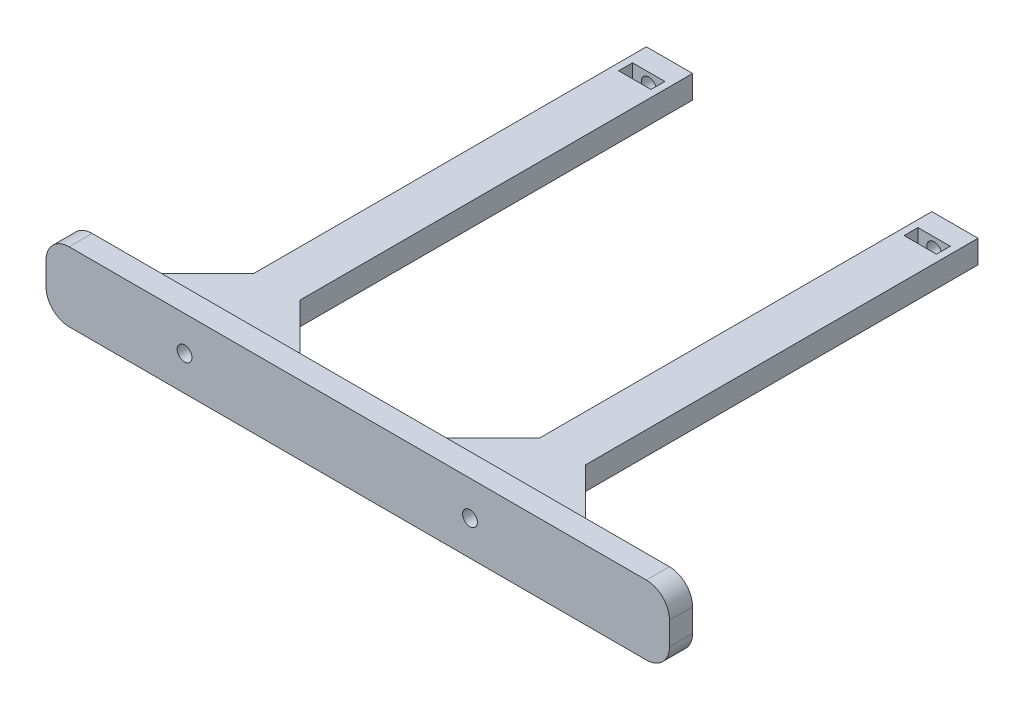
SolidWorks part; units mm, degrees
ref_plane "Plano frontal" through (0, 0, 0) normal (0, 0, 1) x (1, 0, 0)
ref_plane "Plano superior" through (0, 0, 0) normal (0, 1, 0) x (1, 0, 0)
ref_plane "Plano direito" through (0, 0, 0) normal (1, 0, 0) x (0, 0, -1)
sketch "Esboço1" plane through (0, 0, 0) normal (0, 0, 1) x (1, 0, 0)
  line L1 (-57.7659, 9.2429) -> (77.2341, 9.2429)
  line L2 (-57.7659, 9.2429) -> (-57.7659, -5.7571)
  line L3 (-57.7659, -5.7571) -> (77.2341, -5.7571)
  line L4 (77.2341, 9.2429) -> (77.2341, -5.7571)
extrude "Ressalto-extrusão1" add sketch "Esboço1" along normal blind 5
fillet "Filete1" radius 5 2 edges at (-57.7659, -5.7571, 2.5) (-57.7659, 9.2429, 2.5)
fillet "Filete2" radius 5 2 edges at (77.2341, 9.2429, 2.5) (77.2341, -5.7571, 2.5)
sketch "Esboço3" plane through (0, 0, 0) normal (0, 0, -1) x (-1, 0, 0)
  line L0 (57.7659, 1.7429) -> (27.7659, 1.7429) construction
  line L1 (57.7659, 4.2429) -> (57.7659, -0.7571) construction
  line L2 (27.7659, 1.7429) -> (-34.0341, 1.7429) construction
  circle A0 centre (27.7659, 1.7429) radius 1.6
  circle A1 centre (-34.0341, 1.7429) radius 1.6
extrude "Corte-extrusão1" cut sketch "Esboço3" against normal blind 5
sketch "Esboço5" plane through (0, 0, 0) normal (0, 0, -1) x (-1, 0, 0)
  line L1 (-39.0341, -0.7571) -> (-29.0341, -0.7571)
  line L2 (-39.0341, -0.7571) -> (-39.0341, 4.2429)
  line L3 (-39.0341, 4.2429) -> (-29.0341, 4.2429)
  line L4 (-29.0341, -0.7571) -> (-29.0341, 4.2429)
  line L5 (-39.0341, -0.7571) -> (-29.0341, 4.2429) construction
  line L6 (-39.0341, 4.2429) -> (-29.0341, -0.7571) construction
  line L7 (22.7659, -0.7571) -> (32.7659, -0.7571)
  line L8 (22.7659, -0.7571) -> (22.7659, 4.2429)
  line L9 (22.7659, 4.2429) -> (32.7659, 4.2429)
  line L10 (32.7659, -0.7571) -> (32.7659, 4.2429)
  line L11 (22.7659, -0.7571) -> (32.7659, 4.2429) construction
  line L12 (22.7659, 4.2429) -> (32.7659, -0.7571) construction
  point P0 (-34.0341, 1.7429)
  point P5 (27.7659, 1.7429)
extrude "Ressalto-extrusão4" add sketch "Esboço5" along normal blind 100
sketch "Esboço6" plane through (0, 4.2429, 0) normal (0, 1, 0) x (1, 0, 0)
  line L0 (34.0341, 100) -> (34.0341, 94) construction
  line L1 (29.0341, 100) -> (39.0341, 100) construction
  line L2 (-27.7659, 100) -> (-27.7659, 94) construction
  line L3 (-32.7659, 100) -> (-22.7659, 100) construction
  line L5 (37.5341, 95.5) -> (30.5341, 95.5)
  line L6 (37.5341, 95.5) -> (37.5341, 92.5)
  line L7 (37.5341, 92.5) -> (30.5341, 92.5)
  line L8 (30.5341, 95.5) -> (30.5341, 92.5)
  line L9 (37.5341, 95.5) -> (30.5341, 92.5) construction
  line L10 (37.5341, 92.5) -> (30.5341, 95.5) construction
ref_plane "Plano1" through (0, 1.7429, 0) normal (0, 1, 0) x (1, 0, 0)
sketch "Esboço7" plane through (0, 1.7429, 0) normal (0, 1, 0) x (1, 0, 0)
  line L0 (-32.7659, 100) -> (-32.7659, 0) construction
  line L1 (-32.7659, 15) -> (-32.7659, 0)
  line L2 (72.2341, 0) -> (-52.7659, 0) construction
  line L3 (-32.7659, 0) -> (-47.7659, 0)
  line L4 (-32.7659, 15) -> (-47.7659, 0)
extrude "Ressalto-extrusão5" add sketch "Esboço7" along normal up to vertex and the other way up to vertex
sketch "Esboço8" plane through (0, 4.2429, 0) normal (0, 1, 0) x (1, 0, 0)
  line L0 (39.0341, 100) -> (39.0341, 0) construction
  line L1 (39.0341, 15) -> (39.0341, 0)
  line L2 (72.2341, 0) -> (-52.7659, 0) construction
  line L3 (54.0341, 0) -> (39.0341, 0)
  line L4 (54.0341, 0) -> (39.0341, 15)
extrude "Ressalto-extrusão6" add sketch "Esboço8" against normal up to surface (5 mm away) up to face at (34.0341, -0.7571, -50)
sketch "Esboço9" plane through (0, 1.7429, 0) normal (0, 1, 0) x (1, 0, 0)
  line L0 (29.0341, 100) -> (29.0341, 0) construction
  line L1 (29.0341, 15) -> (29.0341, 0)
  line L2 (72.2341, 0) -> (-52.7659, 0) construction
  line L3 (72.2341, 0) -> (54.0341, 0)
  line L4 (54.0341, 0) -> (39.0341, 15) construction
  line L5 (54.0341, 0) -> (39.0341, 15)
  line L7 (29.0341, 15) -> (14.0341, 0)
  line L8 (29.0341, 0) -> (14.0341, 0)
  line L9 (-22.7659, 100) -> (-22.7659, 0) construction
  line L10 (-22.7659, 15) -> (-22.7659, 0)
  line L11 (72.2341, 0) -> (54.0341, 0)
  line L12 (-7.7659, 0) -> (-22.7659, 15)
  line L13 (-7.7659, 0) -> (-22.7659, 0)
  line L14 (29.0341, 0) -> (14.0341, 0)
extrude "Ressalto-extrusão7" add sketch "Esboço9" along normal up to vertex and the other way up to vertex contours L8 L1 L7 | L13 L12 L10
sketch "Esboço10" plane through (0, 1.7429, 0) normal (0, 1, 0) x (1, 0, 0)
  line L0 (29.0341, 100) -> (29.0341, 15) construction
  line L1 (-22.7659, 100) -> (-22.7659, 15) construction
  line L2 (29.0341, 100) -> (29.0341, 15)
  line L3 (-22.7659, 100) -> (-22.7659, 15)
  line L4 (29.0341, 57.5) -> (-22.7659, 57.5) construction
  line L5 (3.1341, 57.5) -> (3.1341, 70.4956) construction
  line L6 (37.5341, 95.5) -> (30.5341, 95.5) construction
  line L7 (37.5341, 92.5) -> (30.5341, 92.5) construction
  line L8 (30.5341, 95.5) -> (30.5341, 92.5) construction
  line L9 (37.5341, 95.5) -> (37.5341, 92.5) construction
  line L10 (37.5341, 95.5) -> (30.5341, 95.5)
  line L11 (37.5341, 92.5) -> (30.5341, 92.5)
  line L12 (30.5341, 95.5) -> (30.5341, 92.5)
  line L13 (37.5341, 95.5) -> (37.5341, 92.5)
  line L14 (-31.2659, 95.5) -> (-31.2659, 92.5)
  line L15 (-24.2659, 95.5) -> (-24.2659, 92.5)
  line L16 (-31.2659, 92.5) -> (-24.2659, 92.5)
  line L17 (-31.2659, 95.5) -> (-24.2659, 95.5)
extrude "Corte-extrusão2" cut sketch "Esboço10" against normal blind 100 and the other way blind 100 contours L17 L14 L16 L15 | L10 L12 L11 L13
sketch "Esboço11" plane through (0, 0, -100) normal (0, 0, -1) x (-1, 0, 0)
  line L0 (32.7659, 4.2429) -> (22.7659, -0.7571) construction
  line L1 (32.7659, -0.7571) -> (22.7659, 4.2429) construction
  line L2 (-39.0341, 4.2429) -> (-29.0341, -0.7571) construction
  line L3 (-39.0341, -0.7571) -> (-29.0341, 4.2429) construction
  circle A0 centre (27.7659, 1.7429) radius 1.6
  circle A1 centre (-34.0341, 1.7429) radius 1.6
extrude "Corte-extrusão3" cut sketch "Esboço11" against normal through all
